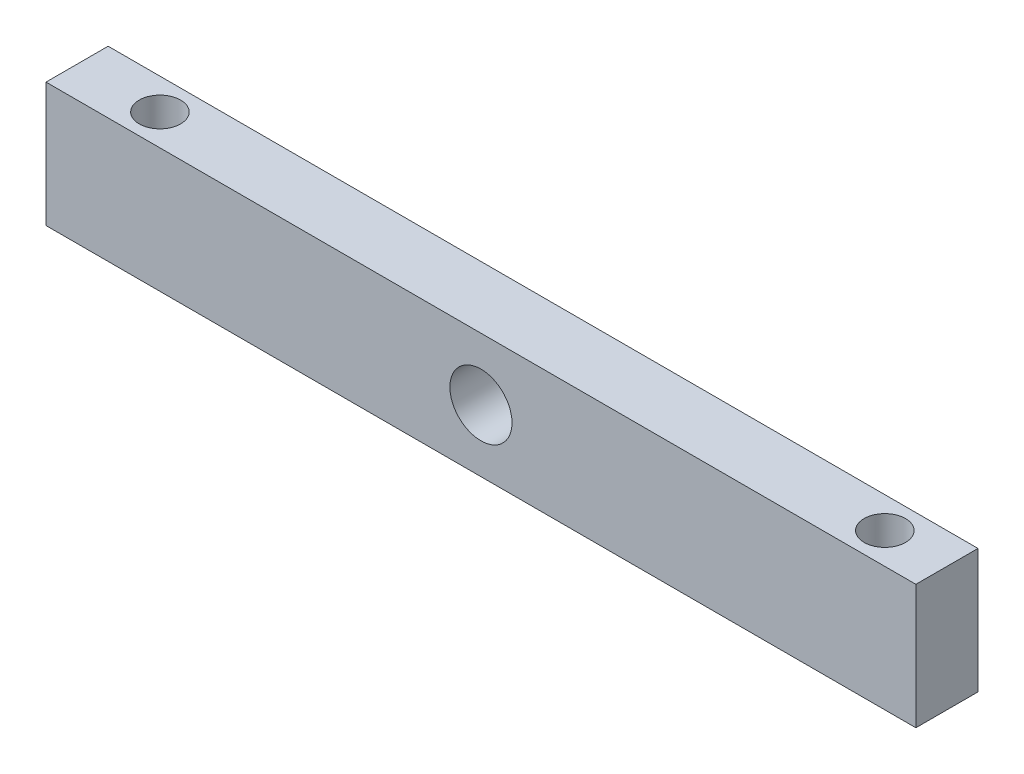
SolidWorks part; units mm, degrees
ref_plane "Plano frontal" through (0, 0, 0) normal (0, 0, 1) x (1, 0, 0)
ref_plane "Plano superior" through (0, 0, 0) normal (0, 1, 0) x (1, 0, 0)
ref_plane "Plano direito" through (0, 0, 0) normal (1, 0, 0) x (0, 0, -1)
sketch "Esboço1" plane through (0, 0, 0) normal (0, 0, 1) x (1, 0, 0)
  line L1 (0, 0) -> (60, 0)
  line L9 (60, 0) -> (60, 30)
  line L10 (60, 30) -> (-150, 30)
  line L11 (-150, 30) -> (-150, 0)
  line L12 (-150, 0) -> (0, 0)
  point P4 (0, 0)
  dimension "D2" = 30
  dimension "D1" = 60
  dimension "D3" = 210
extrude "Ressalto-extrusão1" add sketch "Esboço1" along normal blind 15
sketch "Esboço2" plane through (0, 0, 15) normal (0, 0, 1) x (1, 0, 0)
  line L0 (-45, 0) -> (-45, 30)
  line L1 (-150, 0) -> (60, 0) construction
  line L2 (60, 30) -> (-150, 30) construction
  circle A0 centre (-45, 15) radius 7.5
  dimension "D1" = 15
extrude "Corte-extrusão1" cut sketch "Esboço2" against normal blind 15 contours L0 A0 | L0 A0
sketch "Esboço3" plane through (0, 0, 0) normal (0, -1, 0) x (-1, 0, 0)
  line L0 (150, -7.5) -> (130, -7.5)
  line L1 (150, -15) -> (150, 0) construction
  line L2 (-60, -7.5) -> (-45, -7.5)
  line L3 (-60, -15) -> (-60, 0) construction
  circle A0 centre (130, -7.5) radius 5
  circle A1 centre (-45, -7.5) radius 5
  dimension "D2" = 10
  dimension "D4" = 10
  dimension "D1" = 20
  dimension "D3" = 15
extrude "Corte-extrusão2" cut sketch "Esboço3" against normal blind 30
